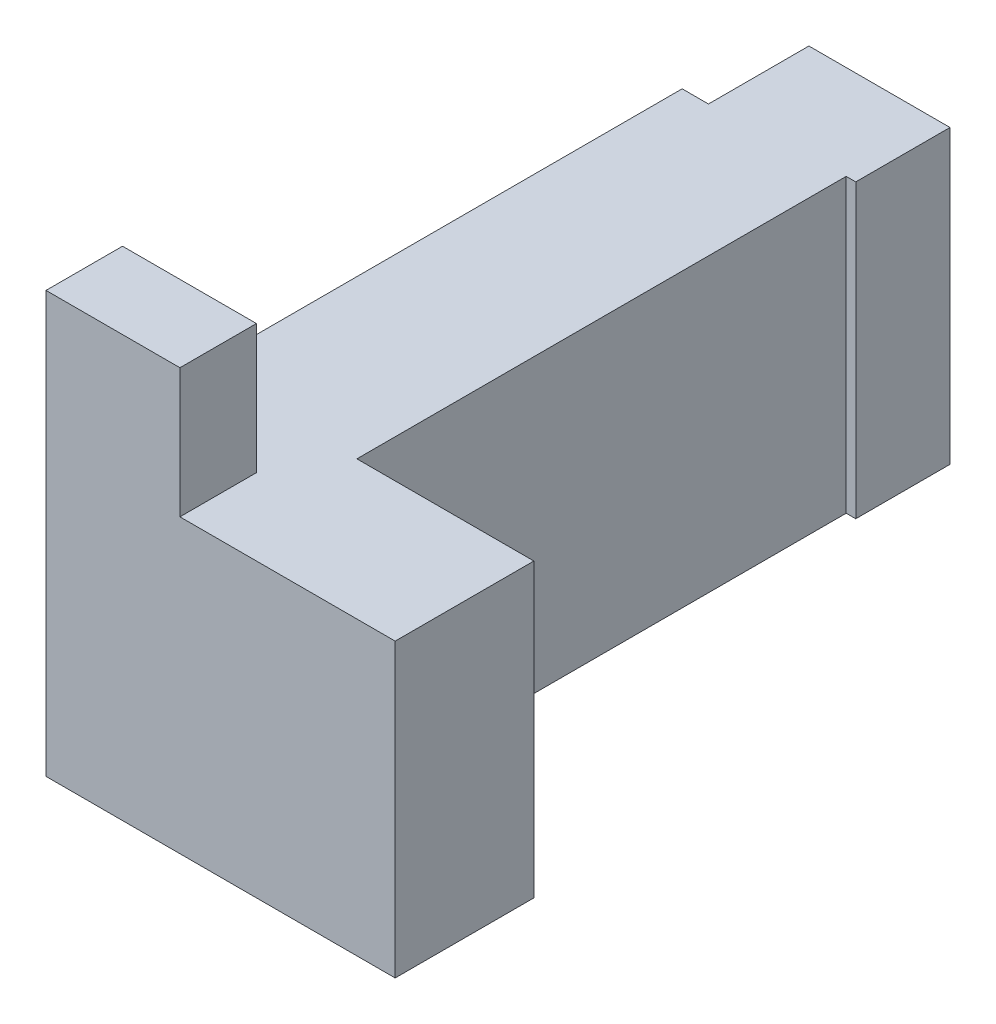
SolidWorks part; units mm, degrees
ref_plane "Front Plane" through (0, 0, 0) normal (0, 0, 1) x (1, 0, 0)
ref_plane "Top Plane" through (0, 0, 0) normal (0, 1, 0) x (1, 0, 0)
ref_plane "Right Plane" through (0, 0, 0) normal (1, 0, 0) x (0, 0, -1)
sketch "Sketch1" plane through (0, 0, 0) normal (0, 1, 0) x (1, 0, 0)
  line L4 (730, 290) -> (360, 290)
  line L5 (360, 290) -> (360, 1312.9576)
  line L6 (360, 1312.9576) -> (380, 1312.9576)
  line L7 (380, 1312.9576) -> (380, 1510)
  line L8 (380, 1510) -> (85, 1510)
  line L9 (85, 1510) -> (85, 1300)
  line L10 (85, 1300) -> (30, 1300)
  line L11 (30, 1300) -> (30, 320)
  line L12 (30, 320) -> (0, 320)
  line L13 (0, 320) -> (0, 0)
  line L14 (730, 290) -> (730, 0)
  line L15 (730, 0) -> (0, 0)
  dimension "D1" = 730
  dimension "D2" = 320
  dimension "D3" = 330
  dimension "D4" = 0
  dimension "D5" = 30
  dimension "D6" = 295
  dimension "D7" = 210
  dimension "D8" = 980
  dimension "D9" = 0
  dimension "D10" = 20
  dimension "D11" = 197.0424
  dimension "D12" = 290
extrude "Boss-Extrude1" add sketch "Sketch1" along normal blind 610
sketch "Sketch2" plane through (0, 610, 0) normal (0, 1, 0) x (1, 0, 0)
  line L0 (0, 0) -> (0, 160)
  line L1 (0, 160) -> (280, 160)
  line L2 (280, 160) -> (280, 0)
  line L3 (280, 0) -> (0, 0)
  dimension "D1" = 160
  dimension "D2" = 0
  dimension "D3" = 280
  dimension "D4" = 0
extrude "Boss-Extrude2" add sketch "Sketch2" along normal blind 270
